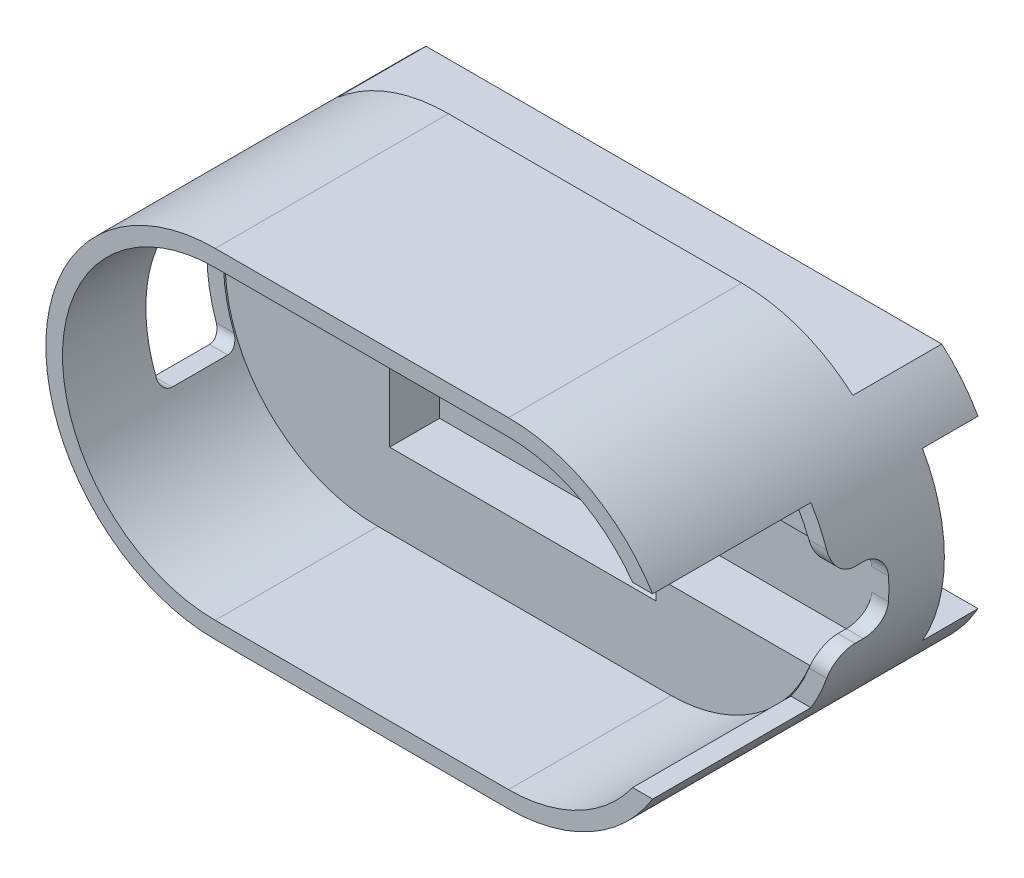
SolidWorks part; units mm, degrees
ref_plane "Front Plane" through (0, 0, 0) normal (0, 0, 1) x (1, 0, 0)
ref_plane "Top Plane" through (0, 0, 0) normal (0, 1, 0) x (1, 0, 0)
ref_plane "Right Plane" through (0, 0, 0) normal (1, 0, 0) x (0, 0, -1)
sketch "Sketch1" plane through (0, 0, 0) normal (0, 0, 1) x (1, 0, 0)
  line L0 (-34.3844, 17.2192) -> (-7.9844, 17.2192)
  line L1 (-34.3844, -10.2808) -> (-7.9844, -10.2808)
  line L2 (-34.3844, 18.7192) -> (-7.9844, 18.7192)
  line L3 (-34.3844, -11.7808) -> (-7.9844, -11.7808)
  arc A0 (-34.3844, 17.2192) -> (-34.3844, -10.2808) centre (-34.3844, 3.4692) ccw
  arc A1 (-7.9844, -10.2808) -> (-7.9844, 17.2192) centre (-7.9844, 3.4692) ccw
  arc A2 (-7.9844, -11.7808) -> (-7.9844, 18.7192) centre (-7.9844, 3.4692) ccw
  arc A3 (-34.3844, 18.7192) -> (-34.3844, -11.7808) centre (-34.3844, 3.4692) ccw
  point P8 (-48.1344, 3.4692)
  point P9 (5.7656, 3.4692)
  dimension "D1" = 27.5
  dimension "D2" = 53.9
  dimension "D3" = 1.5
extrude "Boss-Extrude1" add sketch "Sketch1" along normal blind 19
sketch "Sketch2" plane through (0, 0, 0) normal (0, 0, -1) x (-1, 0, 0)
  line L0 (34.3844, -11.7808) -> (7.9844, -11.7808)
  line L1 (34.3844, 18.7192) -> (7.9844, 18.7192)
  arc A0 (7.9844, 18.7192) -> (7.9844, -11.7808) centre (7.9844, 3.4692) ccw
  arc A1 (34.3844, -11.7808) -> (34.3844, 18.7192) centre (34.3844, 3.4692) ccw
  arc M5 (34.3844, 17.2192) -> (34.3844, -10.2808) centre (34.3844, 3.4692) cw
  line M6 (34.3844, -10.2808) -> (7.9844, -10.2808)
  arc M7 (7.9844, -10.2808) -> (7.9844, 17.2192) centre (7.9844, 3.4692) cw
  line M8 (7.9844, 17.2192) -> (34.3844, 17.2192)
extrude "Boss-Extrude2" add sketch "Sketch2" along normal blind 2 separate body contours A1 A0 M8 M7 M6 | A1 A0 M6 | A1 A0 M8 M6 M5 | A0 A1 | A1 A0 M8
sketch "Sketch3" plane through (0, 0, 0) normal (0, 0, 1) x (1, 0, 0)
  line L0 (-21.1844, 17.2192) -> (-21.1844, -10.2808) construction
  line L1 (-7.9844, 17.2192) -> (-34.3844, 17.2192) construction
  line L2 (-34.3844, -10.2808) -> (-7.9844, -10.2808) construction
  line L3 (-9.1844, 3.4692) -> (4.8328, 3.4692) construction
  line L4 (-33.1844, -3.4308) -> (-9.1844, -3.4308)
  line L5 (-33.1844, -3.4308) -> (-33.1844, 10.3692)
  line L6 (-33.1844, 10.3692) -> (-9.1844, 10.3692)
  line L7 (-9.1844, -3.4308) -> (-9.1844, 10.3692)
  line L8 (-33.1844, -3.4308) -> (-9.1844, 10.3692) construction
  line L9 (-33.1844, 10.3692) -> (-9.1844, -3.4308) construction
  line L10 (-9.1844, -1.5308) -> (4.6632, -1.5308)
  line L11 (-9.1844, 8.4692) -> (4.6632, 8.4692)
  line L12 (-34.3844, 17.0693) -> (-7.9844, 17.0693)
  line L13 (-7.9844, -10.1309) -> (-34.3844, -10.1309)
  line L14 (-9.1844, -1.5308) -> (4.8328, -1.5308) construction
  line L15 (-9.1844, 8.4692) -> (4.8328, 8.4692) construction
  arc A0 (-19.7042, 10.3692) -> (-19.7042, -3.4308) centre (-7.9844, 3.4692) ccw
  arc A1 (-34.3844, 17.0693) -> (-34.3844, -10.1309) centre (-34.3844, 3.4692) ccw
  arc A2 (-7.9844, -10.1309) -> (-7.9844, 17.0693) centre (-7.9844, 3.4692) ccw
  arc A3 (-22.6647, -3.4308) -> (-21.1844, 6.7437) centre (-34.3844, 3.4692) ccw
  point P6 (-21.1844, 3.4692)
  dimension "D1" = 13.8
  dimension "D2" = 24
  dimension "D3" = 5
  dimension "D4" = 5
extrude "Boss-Extrude3" add sketch "Sketch3" along normal blind 4.5 contours L11 A2 L12 A1 L13 L10 L7 L4 L5 L6
sketch "Sketch4" plane through (-9.1844, 0, 0) normal (-1, 0, 0) x (0, 0, 1)
  line L0 (4.5, -1.5308) -> (4.5, 8.4692) construction
  line L1 (4.5, 3.4692) -> (9.0795, 3.4692) construction
  line L2 (0, -3.4308) -> (0, -1.5308) construction
  line L3 (4.75, 11.4692) -> (19, 11.4692)
  line L4 (4.75, 11.4692) -> (4.75, -4.5308)
  line L5 (4.75, -4.5308) -> (19, -4.5308)
  line L6 (19, 11.4692) -> (19, -4.5308)
  line L7 (4.75, 11.4692) -> (19, -4.5308) construction
  line L8 (4.75, -4.5308) -> (19, 11.4692) construction
  line L9 (0, 6.4692) -> (4.75, 6.4692)
  line L10 (0, 6.4692) -> (0, 0.4692)
  line L11 (0, 0.4692) -> (4.75, 0.4692)
  line L12 (4.75, 6.4692) -> (4.75, 0.4692)
  line L13 (0, 6.4692) -> (4.75, 0.4692) construction
  line L14 (0, 0.4692) -> (4.75, 6.4692) construction
  line L15 (19, -10.2808) -> (19, 17.2192) construction
  point P6 (11.875, 3.4692)
  point P11 (2.375, 3.4692)
  dimension "D1" = 16
  dimension "D3" = 0.5
  dimension "D4" = 6
extrude "Cut-Extrude1" cut sketch "Sketch4" against normal through all contours L10 L11 L4 L9 | L6 L3 L4 L5
sketch "Sketch5" plane through (-33.1844, 0, 0) normal (1, 0, 0) x (0, 0, -1)
  line L0 (-4.5, 3.4692) -> (-8.318, 3.4692) construction
  line L1 (-4.5, -3.4308) -> (-4.5, 10.3692) construction
  line L3 (-4.5, -2.5308) -> (-11.5, -2.5308)
  line L4 (-4.5, -2.5308) -> (-4.5, 9.4692)
  line L5 (-4.5, 9.4692) -> (-11.5, 9.4692)
  line L6 (-11.5, -2.5308) -> (-11.5, 9.4692)
  line L7 (-4.5, -2.5308) -> (-11.5, 9.4692) construction
  line L8 (-4.5, 9.4692) -> (-11.5, -2.5308) construction
  point P4 (-8, 3.4692)
  dimension "D1" = 12
  dimension "D2" = 7
extrude "Cut-Extrude2" cut sketch "Sketch5" against normal through all
fillet "Fillet1" radius 1 4 edges at (-47.5804, 9.4692, 4.5) (-47.5804, -2.5308, 4.5) (-47.5804, -2.5308, 11.5) (-47.5804, 9.4692, 11.5)
sketch "Sketch6" plane through (0, 0, -2) normal (0, 0, -1) x (-1, 0, 0)
  line L0 (49.6344, 3.4692) -> (-7.2656, 3.4692) construction
  line L1 (47.6627, 10.9692) -> (-5.2938, 10.9692)
  line L2 (47.6627, -4.0308) -> (-5.2938, -4.0308)
  line L3 (43.1201, -9.0308) -> (-0.7513, -9.0308)
  line L4 (43.1201, 15.9692) -> (-0.7513, 15.9692)
  line L5 (49.6344, -9.0308) -> (-7.2656, -9.0308) construction
  line L6 (49.6344, -4.0308) -> (-7.2656, -4.0308) construction
  line L7 (49.6344, 15.9692) -> (-7.2656, 15.9692) construction
  line L8 (49.6344, 10.9692) -> (-7.2656, 10.9692) construction
  arc A0 (34.3844, -11.7808) -> (34.3844, 18.7192) centre (34.3844, 3.4692) ccw construction
  arc A1 (7.9844, 18.7192) -> (7.9844, -11.7808) centre (7.9844, 3.4692) ccw construction
  arc A2 (43.1201, -9.0308) -> (43.1201, 15.9692) centre (34.3844, 3.4692) ccw
  arc A3 (21.1844, -4.1677) -> (21.1844, 11.1061) centre (7.9844, 3.4692) ccw
  arc A4 (-0.7513, 15.9692) -> (-0.7513, -9.0308) centre (7.9844, 3.4692) ccw
  arc A5 (21.1844, 11.1061) -> (21.1844, -4.1677) centre (34.3844, 3.4692) ccw
  circle A6 centre (21.1844, 3.4692) radius 1.25
  arc M5 (34.3844, -11.7808) -> (34.3844, 18.7192) centre (34.3844, 3.4692) ccw
  arc M7 (7.9844, 18.7192) -> (7.9844, -11.7808) centre (7.9844, 3.4692) ccw
  dimension "D5" = 2.5
  dimension "D1" = 7.5
  dimension "D2" = 7.5
  dimension "D3" = 5
  dimension "D4" = 5
extrude "Boss-Extrude4" add sketch "Sketch6" along normal blind 3 contours A3 L2 L1 M5 | L1 A5 L2 A3 | A5 L1 L2 M7
sketch "Sketch9" plane through (0, 0, -2) normal (0, 0, -1) x (-1, 0, 0)
  circle A0 centre (21.1844, 3.4692) radius 1.2524
  dimension "D1" = 2.5049
sketch "Sketch10" plane through (0, 0, -2) normal (0, 0, -1) x (-1, 0, 0)
  line L0 (-5.2938, -4.0308) -> (47.6627, -4.0308)
  line L1 (47.6627, 10.9692) -> (-5.2938, 10.9692)
  line L2 (44.4001, 14.9692) -> (-2.0312, 14.9692)
  line L3 (-2.0312, -8.0308) -> (44.4001, -8.0308)
  line L4 (-5.2938, -8.0308) -> (47.6627, -8.0308) construction
  line L5 (47.6627, 14.9692) -> (-5.2938, 14.9692) construction
  line L6 (47.6627, 10.9692) -> (-5.2938, 10.9692) construction
  arc A0 (44.4001, -8.0308) -> (47.6627, -4.0308) centre (34.3844, 3.4692) ccw
  arc A1 (47.6627, 10.9692) -> (44.4001, 14.9692) centre (34.3844, 3.4692) ccw
  arc A2 (-2.0312, 14.9692) -> (-5.2938, 10.9692) centre (7.9844, 3.4692) ccw
  arc A3 (-5.2938, -4.0308) -> (-2.0312, -8.0308) centre (7.9844, 3.4692) ccw
  line M2 (-5.2938, 10.9692) -> (47.6627, 10.9692)
  arc M3 (47.6627, 10.9692) -> (34.3844, 18.7192) centre (34.3844, 3.4692) ccw
  arc M5 (7.9844, 18.7192) -> (-5.2938, 10.9692) centre (7.9844, 3.4692) ccw
  dimension "D1" = 4
  dimension "D2" = 4
extrude "Boss-Extrude7" add sketch "Sketch10" along direction (0, 0, -1) on the side of the normal blind 8 contours L0 A3 L3 A0 | L2 M3 M5 M2
fillet "Fillet2" radius 2 4 edges at (6.2009, 0.4692, 0) (6.2009, 6.4692, 0) (6.2009, 6.4692, 4.75) (6.2009, 0.4692, 4.75)
extrude "Cut-Extrude3" cut sketch "Sketch9" against normal blind 10
